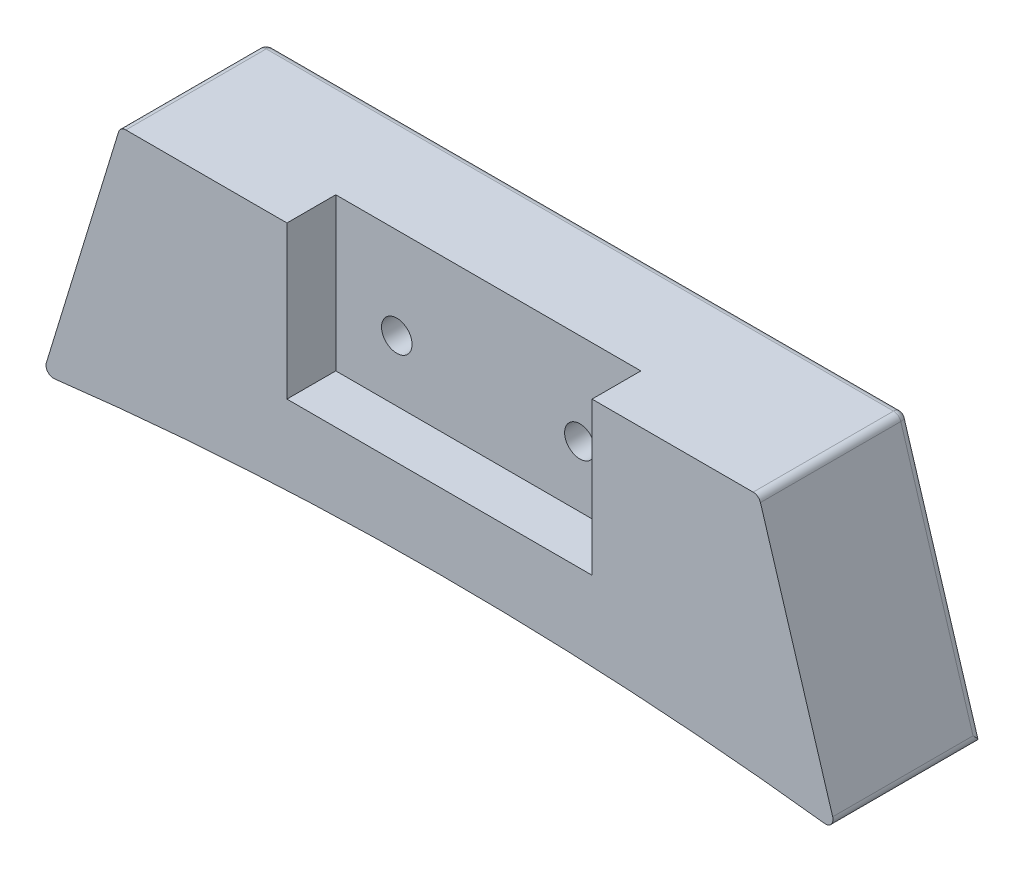
SolidWorks part; units mm, degrees
material "7075-O (SS)"
ref_plane "前视基准面" through (0, 0, 0) normal (0, 0, 1) x (1, 0, 0)
ref_plane "上视基准面" through (0, 0, 0) normal (0, 1, 0) x (1, 0, 0)
ref_plane "右视基准面" through (0, 0, 0) normal (1, 0, 0) x (0, 0, -1)
sketch "草图1" plane through (0, 0, 0) normal (0, 0, 1) x (1, 0, 0)
  line L0 (-21, 14.9488) -> (21, 14.9488)
  line L1 (-21, 14.9488) -> (-28, -3.0512) construction
  line L2 (28, -3.0512) -> (21, 14.9488) construction
  line L3 (0, 170.6556) -> (0, 0) construction
  line L4 (6, 6.9488) -> (-6, 6.9488) construction
  line L5 (0, 0) -> (30.5, 0) construction
  line L6 (30.5, 0) -> (30.5, -4) construction
  line L7 (30.5, -4) -> (-32, -4) construction
  line L8 (21, 14.9488) -> (23.5, 14.9488)
  line L9 (23.5, 14.9488) -> (26, -1.6157)
  line L10 (-21, 14.9488) -> (-23.5, 14.9488)
  line L11 (-23.5, 14.9488) -> (-26, -1.6157)
  line L12 (0, 170.6556) -> (-23.5, 14.9488) construction
  line L13 (0, 170.6556) -> (23.5, 14.9488) construction
  arc A0 (-28, -3.0512) -> (28, -3.0512) centre (0, -130) cw construction
  circle A1 centre (-6, 6.9488) radius 0.5 construction
  circle A2 centre (6, 6.9488) radius 0.5 construction
  arc A3 (26, -1.6157) -> (-26, -1.6157) centre (0, -210) ccw
  point P10 (0, 6.9488)
  dimension "D3" = 130
  dimension "D2" = 1
  dimension "D5" = 12
  dimension "D6" = 1
  dimension "D7" = 2.5
  dimension "D8" = 8
  dimension "D12" = 210
  dimension "D1" = 42
  dimension "D4" = 56
  dimension "D9" = 18
  dimension "D10" = 2.5
  dimension "D11" = 26
  dimension "D13" = 26
extrude "凸台-拉伸1" add sketch "草图1" along normal blind 9.7
sketch "草图2" plane through (0, 14.9488, 0) normal (0, 1, 0) x (1, 0, 0)
  line L1 (23.5, 0) -> (-23.5, 0) construction
  line L2 (6, 2) -> (-6, 2)
  line L3 (6, 2) -> (6, -2)
  line L4 (6, -2) -> (-6, -2)
  line L5 (-6, 2) -> (-6, -2)
  line L6 (6, 2) -> (-6, -2) construction
  line L7 (6, -2) -> (-6, 2) construction
  point P0 (0, 0)
  dimension "D1" = 12
  dimension "D2" = 4
extrude "切除-拉伸1" [suppressed] cut sketch "草图2" against normal through all
fillet "圆角1" [suppressed] radius 1
hole_wizard "M3 螺纹孔1" [suppressed] positions "草图8" profile "草图9" tap size "M3" standard "GB"
sketch "草图8" plane through (0, 14.9016, 0) normal (0, 1, 0) x (-1, 0, 0)
  line L2 (-24.6362, 0) -> (24.3638, 0) construction
  point P0 (-16.5, 3)
  point P2 (16.5, 3)
  dimension "D1" = 33
  dimension "D2" = 16.5
  dimension "D3" = 3
sketch "草图9" plane through (16.5, 14.9016, 3) normal (1, 0, 0) x (0, 0, 1)
  line L0 (0, 0) -> (0, 8.2511)
  line L1 (0, 8.2511) -> (1.25, 7.5)
  line L2 (1.25, 7.5) -> (1.25, 0)
  line L5 (1.25, 0) -> (0, 0)
  line L10 (0, 8.2511) -> (-1.25, 7.5) construction
  line L11 (0, -6.35) -> (0, 107.95) construction
  dimension "螺纹孔钻头直径" = 2.5
  dimension "螺纹孔钻头深度" = 7.5
  dimension "导头角度" = 118
cosmetic thread "孔螺蚊线1" [suppressed] parameters "D1"=6, "D2"=3
cosmetic thread "孔螺蚊线3" [suppressed] parameters "D1"=6, "D2"=3
sketch "草图10" plane through (0, 0, 9.7) normal (0, 0, 1) x (1, 0, 0)
  line L0 (26, -1.6157) -> (20.9148, 15.0031)
  line L1 (23.5, 14.9488) -> (26, -1.6157)
  line L2 (20.9148, 15.0031) -> (23.5, 14.9488)
extrude "切除-拉伸2" cut sketch "草图10" against normal through all
mirror "镜向1" about plane through (0, 0, 0) normal (1, 0, 0) of "切除-拉伸2"
chamfer "倒角1" [suppressed] distance 0.5 angle 45
chamfer "倒角2" [suppressed] distance 0.2 angle 45
sketch "草图12" plane through (0, 0, 0) normal (0, 0, -1) x (-1, 0, 0)
  line L1 (-38.9385, -22.4667) -> (31.0262, -22.4667)
  line L2 (-38.9385, -22.4667) -> (-38.9385, 27.9216)
  line L3 (-38.9385, 27.9216) -> (31.0262, 27.9216)
  line L4 (31.0262, -22.4667) -> (31.0262, 27.9216)
extrude "切除-拉伸4" [suppressed] cut sketch "草图12" against normal blind 1.5
fillet "圆角3" radius 0.5 7 edges at (-20.9315, 14.9488, 4.85) (20.9315, 14.9488, 4.85) (-23.4657, 6.6665, 0) (23.4657, 6.6665, 0) (0, 14.9488, 0) (-26, -1.6157, 4.85) (26, -1.6157, 4.85)
sketch "草图13" plane through (0, 0, 9.7) normal (0, 0, 1) x (1, 0, 0)
  line L0 (-3.85, 14.9488) -> (-3.85, 3.9488)
  line L1 (20.5616, 14.9488) -> (-20.5616, 14.9488) construction
  line L2 (-3.85, 3.9488) -> (3.85, 3.9488)
  line L3 (3.85, 3.9488) -> (3.85, 14.9488)
  line L4 (0, 14.9488) -> (0, 3.9488) construction
  line L5 (-3.85, 14.9488) -> (3.85, 14.9488)
  dimension "D1" = 7.7
  dimension "D2" = 11
extrude "安装槽" [suppressed] cut sketch "草图13" against normal blind 5
sketch "草图14" [suppressed] plane through (0, 0, 4.7) normal (0, 0, 1) x (1, 0, 0)
  line L0 (-3.85, 9.4488) -> (3.85, 9.4488) construction
  line L1 (-3.85, 14.9488) -> (-3.85, 3.9488) construction
  line L2 (3.85, 3.9488) -> (3.85, 14.9488) construction
  line L3 (0, 14.9488) -> (0, 3.9488) construction
  line L4 (3.85, 14.9488) -> (-3.85, 14.9488) construction
  line L5 (-3.85, 3.9488) -> (3.85, 3.9488) construction
  line L8 (0, 6.4016) -> (0, 9.4488) construction
  circle A0 centre (0, 9.4488) radius 1.5
  point P12 (0, 9.4488)
  dimension "D3" = 3
extrude "安装孔上半部分" [suppressed] cut sketch "草图14" against normal blind 5
sketch "草图16" [suppressed] plane through (0, 0, 0) normal (0, 0, -1) x (-1, 0, 0)
  circle A1 centre (0, 9.4488) radius 2.5
  dimension "D1" = 5
extrude "安装孔下半部分" [suppressed] cut sketch "草图16" against normal blind 3
sketch "草图17" plane through (0, 0, 9.7) normal (0, 0, 1) x (1, 0, 0)
  line L0 (-10, 14.9488) -> (-10, 4.9488)
  line L1 (20.5616, 14.9488) -> (-20.5616, 14.9488) construction
  line L2 (-10, 4.9488) -> (10, 4.9488)
  line L3 (10, 4.9488) -> (10, 14.9488)
  line L4 (0, 14.9488) -> (0, 2.2565) construction
  line L5 (0, 4.9488) -> (0, 14.9488) construction
  dimension "D1" = 20
  dimension "D2" = 10
extrude "切除-拉伸5" cut sketch "草图17" against normal blind 3.2 and the other way through all
sketch "草图18" plane through (0, 0, 6.5) normal (0, 0, 1) x (1, 0, 0)
  line L0 (-10, 4.9488) -> (10, 4.9488) construction
  line L1 (0, 14.9488) -> (0, 4.9488) construction
  line L2 (10, 14.9488) -> (-10, 14.9488) construction
  line L3 (-10, 4.9488) -> (10, 4.9488) construction
  circle A0 centre (-6, 8.9488) radius 1
  circle A1 centre (6, 8.9488) radius 1
  dimension "D1" = 2
  dimension "D2" = 12
  dimension "D3" = 4
  dimension "D4" = 6
extrude "切除-拉伸6" cut sketch "草图18" against normal through all
cosmetic thread "装饰螺纹线2" parameters "D1"=7, "D2"=3
cosmetic thread "装饰螺纹线3" parameters "D1"=7, "D2"=3
